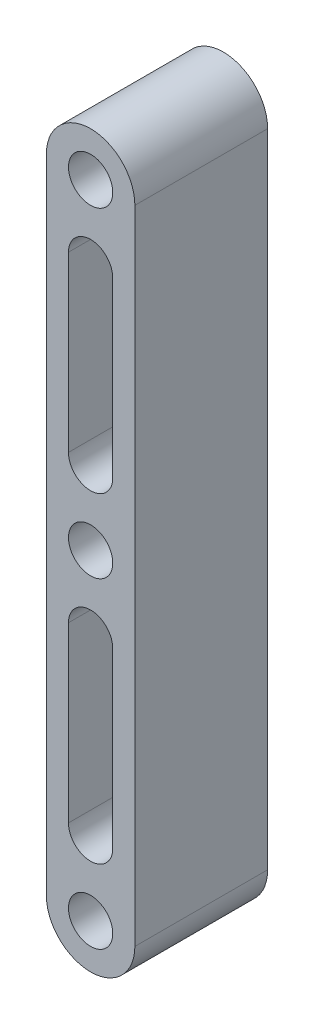
SolidWorks part; units mm, degrees
material "PBT General Purpose"
ref_plane "Front Plane" through (0, 0, 0) normal (0, 0, 1) x (1, 0, 0)
ref_plane "Top Plane" through (0, 0, 0) normal (0, 1, 0) x (1, 0, 0)
ref_plane "Right Plane" through (0, 0, 0) normal (1, 0, 0) x (0, 0, -1)
sketch "Sketch1" plane through (0, 0, 0) normal (0, 0, 1) x (1, 0, 0)
  line L0 (0, 0) -> (0, -87) construction
  line L1 (6, 0) -> (6, -87)
  line L2 (-6, 0) -> (-6, -87)
  line L3 (0, -10) -> (0, -33.5) construction
  line L4 (3, -10) -> (3, -33.5)
  line L5 (-3, -10) -> (-3, -33.5)
  line L6 (0, -53.5) -> (0, -77) construction
  line L7 (3, -53.5) -> (3, -77)
  line L8 (-3, -53.5) -> (-3, -77)
  arc A0 (6, 0) -> (-6, 0) centre (0, 0) ccw
  arc A1 (-6, -87) -> (6, -87) centre (0, -87) ccw
  circle A2 centre (0, -87) radius 3
  circle A3 centre (0, 0) radius 3
  circle A4 centre (0, -43.5) radius 3
  arc A5 (3, -10) -> (-3, -10) centre (0, -10) ccw
  arc A6 (-3, -33.5) -> (3, -33.5) centre (0, -33.5) ccw
  arc A7 (3, -53.5) -> (-3, -53.5) centre (0, -53.5) ccw
  arc A8 (-3, -77) -> (3, -77) centre (0, -77) ccw
  point P3 (0, -43.5)
  point P16 (0, -21.75)
  point P21 (0, -65.25)
  dimension "D1" = 6
  dimension "D2" = 6
  dimension "D3" = 43.5
  dimension "D4" = 10
  dimension "D5" = 10
  dimension "D6" = 10
  dimension "D7" = 10
extrude "Boss-Extrude1" add sketch "Sketch1" along normal mid plane 18
equation "\"D5@Sketch1\"=\"D4@Sketch1\""
equation "\"D6@Sketch1\"=\"D4@Sketch1\""
equation "\"D7@Sketch1\"=\"D4@Sketch1\""
